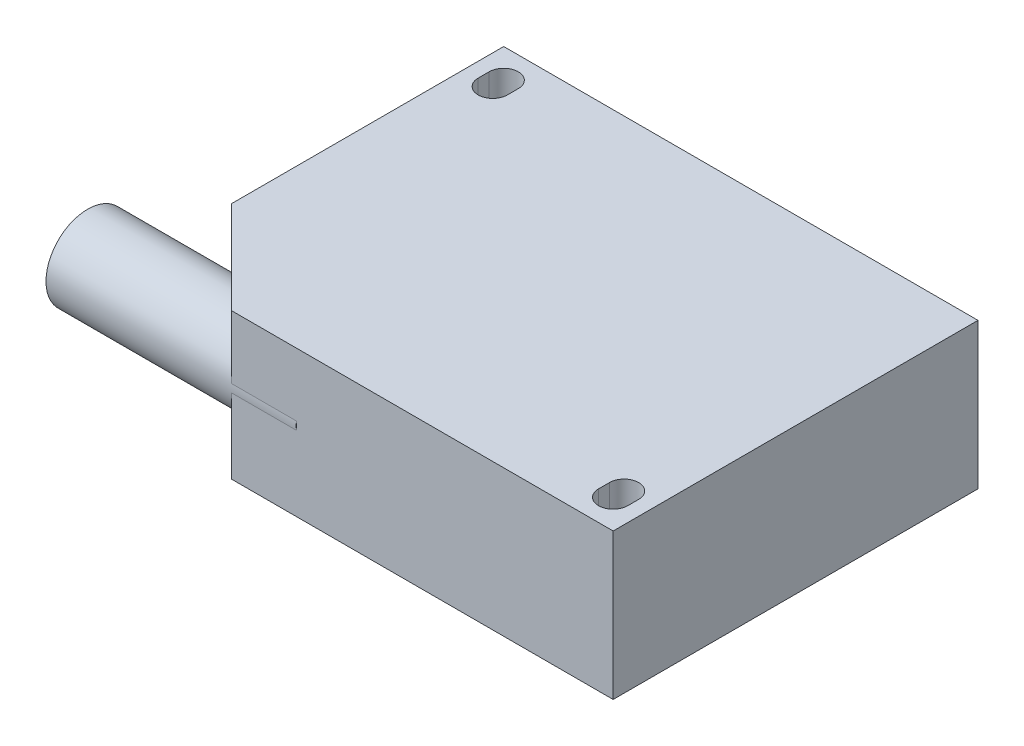
SolidWorks part; units mm, degrees
ref_plane "Front Plane" through (0, 0, 0) normal (0, 0, 1) x (1, 0, 0)
ref_plane "Top Plane" through (0, 0, 0) normal (0, 1, 0) x (1, 0, 0)
ref_plane "Right Plane" through (0, 0, 0) normal (1, 0, 0) x (0, 0, -1)
sketch "Sketch1" plane through (0, 0, 0) normal (0, 1, 0) x (1, 0, 0)
  line L0 (-32.5, -12.3) -> (-19.8, -25)
  line L1 (-32.5, 25) -> (32.5, 25)
  line L2 (-32.5, 25) -> (-32.5, -12.3)
  line L3 (-19.8, -25) -> (32.5, -25)
  line L4 (32.5, 25) -> (32.5, -25)
  line L5 (-32.5, 25) -> (32.5, -25) construction
  line L6 (-32.5, -25) -> (32.5, 25) construction
  point P0 (0, 0)
  dimension "D1" = 50
  dimension "D2" = 65
extrude "Boss-Extrude1" add sketch "Sketch1" along normal blind 20
sketch "Sketch2" plane through (-32.5, 0, 0) normal (-1, 0, 0) x (0, 0, 1)
  circle A0 centre (19.3164, 10.795) radius 5.7104
extrude "Boss-Extrude2" add sketch "Sketch2" along normal blind 12.7 and the other way blind 21.59
sketch "Sketch3" plane through (0, 20, 0) normal (0, 1, 0) x (1, 0, 0)
  line L0 (28.5, -19.5) -> (28.5, -21) construction
  line L1 (30.5, -19.5) -> (30.5, -21)
  line L2 (26.5, -19.5) -> (26.5, -21)
  line L3 (32.5, -25) -> (32.5, 25) construction
  line L5 (-19.8, -25) -> (32.5, -25) construction
  line L6 (-28.5, 21) -> (-28.5, 19.5) construction
  line L7 (-26.5, 21) -> (-26.5, 19.5)
  line L8 (-30.5, 21) -> (-30.5, 19.5)
  line L9 (32.5, 25) -> (-32.5, 25) construction
  line L10 (-32.5, 25) -> (-32.5, -12.3) construction
  arc A0 (30.5, -19.5) -> (26.5, -19.5) centre (28.5, -19.5) ccw
  arc A1 (26.5, -21) -> (30.5, -21) centre (28.5, -21) ccw
  arc A2 (-26.5, 21) -> (-30.5, 21) centre (-28.5, 21) ccw
  arc A3 (-30.5, 19.5) -> (-26.5, 19.5) centre (-28.5, 19.5) ccw
  point P2 (28.5, -20.25)
  point P13 (-28.5, 20.25)
  dimension "D1" = 4
  dimension "D2" = 4
  dimension "D3" = 1.5
  dimension "D4" = 4
  dimension "D5" = 4
  dimension "D6" = 5.5
extrude "Cut-Extrude1" cut sketch "Sketch3" against normal through all
